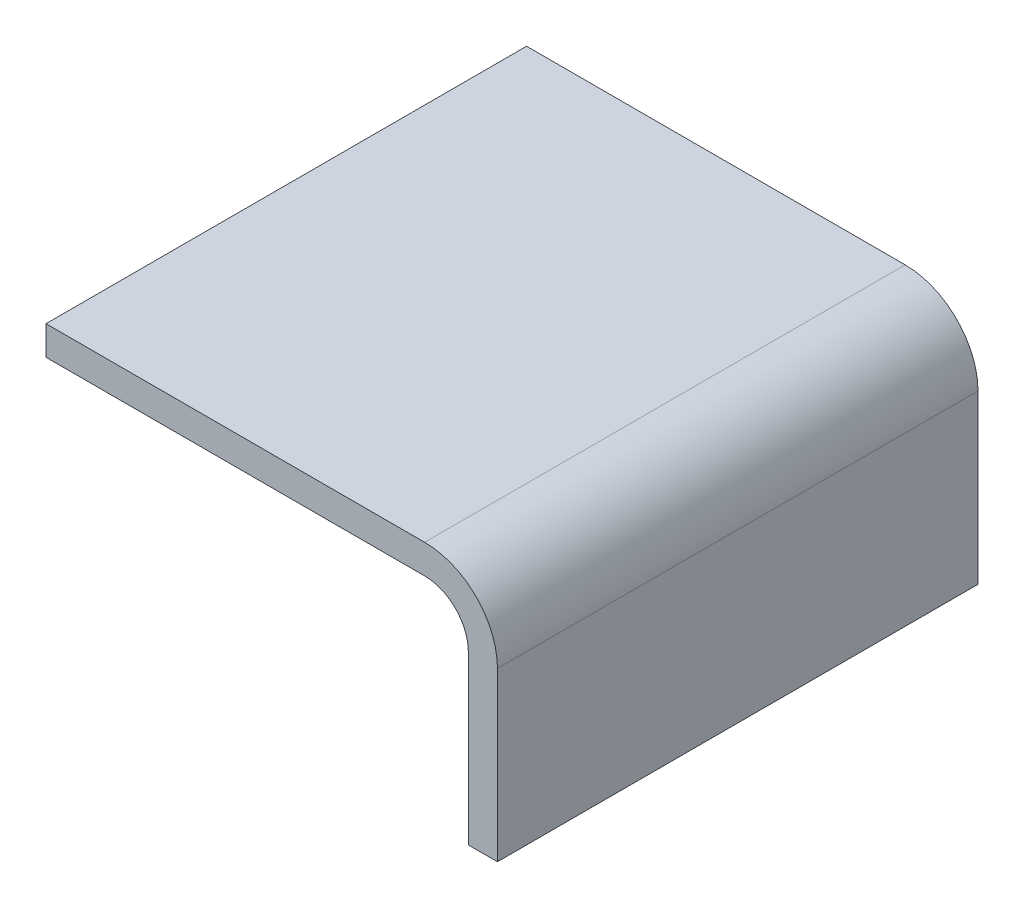
SolidWorks part; units mm, degrees
ref_plane "Front Plane" through (0, 0, 0) normal (0, 0, 1) x (1, 0, 0)
ref_plane "Top Plane" through (0, 0, 0) normal (0, 1, 0) x (1, 0, 0)
ref_plane "Right Plane" through (0, 0, 0) normal (1, 0, 0) x (0, 0, -1)
sketch "Sketch1" plane through (0, 0, 0) normal (0, 0, 1) x (1, 0, 0)
  line L0 (0, 29) -> (52, 29)
  line L3 (0, 33) -> (52, 33)
  line L4 (62, 0) -> (62, 23)
  line L5 (58, 0) -> (58, 23)
  line L6 (62, 0) -> (58, 0)
  line L7 (0, 33) -> (0, 29)
  arc A0 (52, 33) -> (62, 23) centre (52, 23) cw
  arc A1 (52, 29) -> (58, 23) centre (52, 23) cw
  point P6 (62, 33)
  dimension "D3" = 10
  dimension "D1" = 33
  dimension "D2" = 62
  dimension "D4" = 4
extrude "Boss-Extrude1" add sketch "Sketch1" along normal blind 66
